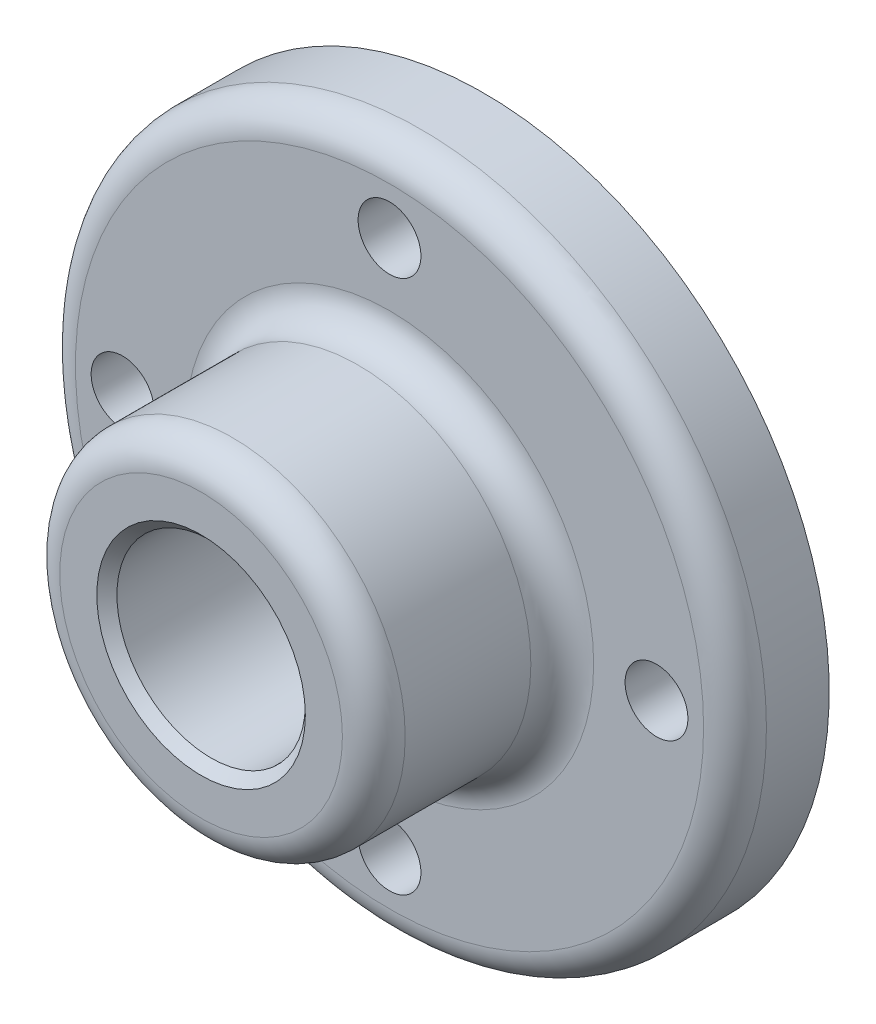
SolidWorks part; units mm, degrees
ref_plane "Front Plane" through (0, 0, 0) normal (0, 0, 1) x (1, 0, 0)
ref_plane "Top Plane" through (0, 0, 0) normal (0, 1, 0) x (1, 0, 0)
ref_plane "Right Plane" through (0, 0, 0) normal (1, 0, 0) x (0, 0, -1)
sketch "Sketch1" plane through (0, 0, 0) normal (0, 0, 1) x (1, 0, 0)
  circle A0 centre (0, 0) radius 69.85
  dimension "D1" = 139.7
extrude "Boss-Extrude1" add sketch "Sketch1" along normal blind 19.05
ref_plane "Plane1" through (0, 0, 57.15) normal (0, 0, 1) x (1, 0, 0)
sketch "Sketch2" plane through (0, 0, 57.15) normal (0, 0, 1) x (1, 0, 0)
  circle A0 centre (0, 0) radius 34.925
  dimension "D1" = 69.85
extrude "Boss-Extrude2" add sketch "Sketch2" against normal up to surface (38.1 mm away) up to face at (69.85, 0, 19.05)
sketch "Sketch3" plane through (0, 0, 57.15) normal (0, 0, 1) x (1, 0, 0)
  circle A0 centre (0, 0) radius 19.05
  dimension "D1" = 38.1
extrude "Cut-Extrude1" cut sketch "Sketch3" against normal through all
sketch "Sketch4" plane through (0, 0, 19.05) normal (0, 0, 1) x (1, 0, 0)
  circle A0 centre (0, 0) radius 53.975 construction
  circle A1 centre (0, 53.975) radius 6.35
  circle A2 centre (53.975, 0) radius 6.35
  circle A3 centre (0, -53.975) radius 6.35
  circle A4 centre (-53.975, 0) radius 6.35
  point P14 (0, 0)
  dimension "D1" = 107.95
  dimension "D2" = 12.7
  dimension "D3" = 4
extrude "Cut-Extrude2" cut sketch "Sketch4" against normal through all
fillet "Fillet1" radius 6.35 3 edges at (34.925, 0, 57.15) (34.925, 0, 19.05) (69.85, 0, 19.05)
chamfer "Chamfer1" distance 2.032 angle 45 1 edges at (19.05, 0, 57.15)
